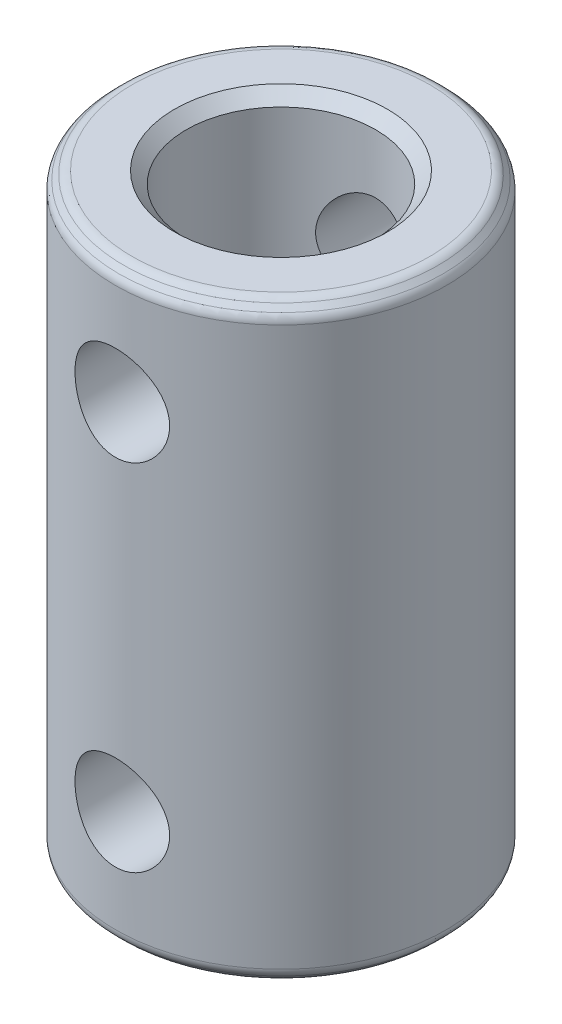
SolidWorks part; units mm, degrees
material "6063-T6, pręt (SS)"
ref_plane "Płaszczyzna przednia" through (0, 0, 0) normal (0, 0, 1) x (1, 0, 0)
ref_plane "Płaszczyzna górna" through (0, 0, 0) normal (0, 1, 0) x (1, 0, 0)
ref_plane "Płaszczyzna prawa" through (0, 0, 0) normal (1, 0, 0) x (0, 0, -1)
sketch "Szkic1" plane through (0, 0, 0) normal (0, 0, 1) x (1, 0, 0)
  line L0 (-20.9212, -8.753) -> (-23.9212, -8.753)
  line L1 (-23.9212, -8.753) -> (-23.9212, -33.753)
  line L2 (-23.9212, -33.753) -> (-19.4212, -33.753)
  line L3 (-20.9212, -8.753) -> (-20.9212, -21.753)
  line L4 (-20.9212, -21.753) -> (-19.4212, -21.753)
  line L5 (-19.4212, -21.753) -> (-19.4212, -33.753)
  line L6 (-20.9212, -13.753) -> (-23.9212, -13.753) construction
  line L7 (-19.4212, -28.753) -> (-23.9212, -28.753) construction
  line L8 (-19.4212, -33.753) -> (-16.9212, -33.753) construction
  line L9 (-16.9212, -33.753) -> (-16.9212, -8.753) construction
  line L10 (-16.9212, -8.753) -> (-20.9212, -8.753) construction
  dimension "D1" = 3
  dimension "D2" = 25
  dimension "D3" = 13
  dimension "D4" = 4.5
  dimension "D5" = 5
  dimension "D6" = 5
revolve "Obrót1" add sketch "Szkic1" angle 360 about L9
sketch "Szkic2" plane through (0, 0, 0) normal (0, 0, 1) x (1, 0, 0)
  line L0 (-16.9212, -33.753) -> (-16.9212, -8.753) construction
  circle A0 centre (-16.9212, -13.753) radius 2
  circle A1 centre (-16.9212, -28.753) radius 2
  dimension "D1" = 5
  dimension "D3" = 4
  dimension "D4" = 4
  dimension "D2" = 5
extrude "Wytnij-wyciągnięcie1" cut sketch "Szkic2" against normal through all both and the other way through all
chamfer "Sfazowanie1" distance 0.5 angle 45 4 edges at (-16.9212, -33.753, -7) (-16.9212, -33.753, -2.5) (-16.9212, -8.753, -4) (-16.9212, -8.753, -7)
fillet "Zaokrąglenie1" radius 0.5 4 edges at (-16.9212, -33.753, 6.5) (-16.9212, -33.253, 7) (-16.9212, -9.253, -7) (-16.9212, -8.753, -6.5)
chamfer "Sfazowanie2" distance 0.5 angle 45 1 edges at (-16.9212, -21.753, -2.5)
